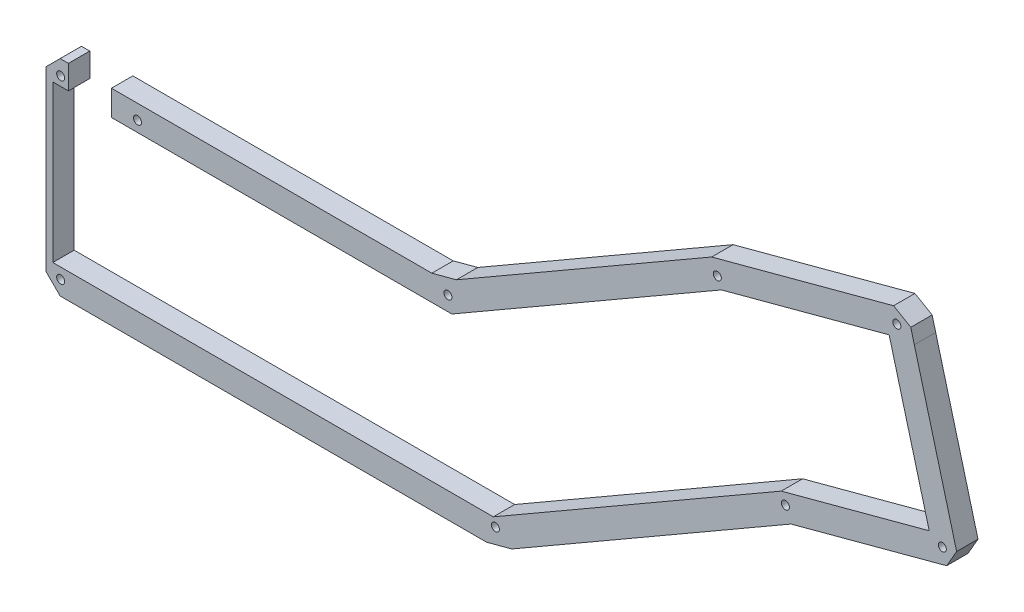
SolidWorks part; units mm, degrees
ref_plane "Plan de face" through (0, 0, 0) normal (0, 0, 1) x (1, 0, 0)
ref_plane "Plan de dessus" through (0, 0, 0) normal (0, 1, 0) x (1, 0, 0)
ref_plane "Plan de droite" through (0, 0, 0) normal (1, 0, 0) x (0, 0, -1)
sketch "Esquisse1" plane through (0, 0, 0) normal (0, 0, 1) x (1, 0, 0)
  line L0 (-73.9886, 18.0851) -> (-59.9886, 18.0851) construction
  line L1 (-73.9886, 37.0851) -> (-59.9886, 37.0851) construction
  line L2 (-73.9886, 37.0851) -> (-73.9886, 23.0851) construction
  line L3 (-73.9886, 23.0851) -> (-59.9886, 23.0851) construction
  line L4 (-59.9886, 37.0851) -> (-59.9886, 23.0851) construction
  line L5 (-73.9886, 18.0851) -> (-73.9886, 4.0851) construction
  line L6 (-73.9886, 4.0851) -> (-59.9886, 4.0851) construction
  line L7 (-59.9886, 18.0851) -> (-59.9886, 4.0851) construction
  line L8 (-73.9886, -0.9149) -> (-59.9886, -0.9149) construction
  line L9 (-73.9886, -0.9149) -> (-73.9886, -14.9149) construction
  line L10 (-73.9886, -14.9149) -> (-59.9886, -14.9149) construction
  line L11 (-59.9886, -0.9149) -> (-59.9886, -14.9149) construction
  line L12 (-73.9886, 37.0851) -> (-73.9886, 18.0851) construction
  line L13 (-54.9886, 18.0851) -> (-40.9886, 18.0851) construction
  line L14 (-54.9886, 37.0851) -> (-40.9886, 37.0851) construction
  line L15 (-54.9886, 37.0851) -> (-54.9886, 23.0851) construction
  line L16 (-54.9886, 23.0851) -> (-40.9886, 23.0851) construction
  line L17 (-40.9886, 37.0851) -> (-40.9886, 23.0851) construction
  line L18 (-54.9886, 18.0851) -> (-54.9886, 4.0851) construction
  line L19 (-54.9886, 4.0851) -> (-40.9886, 4.0851) construction
  line L20 (-40.9886, 18.0851) -> (-40.9886, 4.0851) construction
  line L21 (-54.9886, -0.9149) -> (-40.9886, -0.9149) construction
  line L22 (-54.9886, -0.9149) -> (-54.9886, -14.9149) construction
  line L23 (-54.9886, -14.9149) -> (-40.9886, -14.9149) construction
  line L24 (-40.9886, -0.9149) -> (-40.9886, -14.9149) construction
  line L25 (-54.9886, 37.0851) -> (-54.9886, 18.0851) construction
  line L26 (-35.9886, 18.0851) -> (-21.9886, 18.0851) construction
  line L27 (-35.9886, 37.0851) -> (-21.9886, 37.0851) construction
  line L28 (-35.9886, 37.0851) -> (-35.9886, 23.0851) construction
  line L29 (-35.9886, 23.0851) -> (-21.9886, 23.0851) construction
  line L30 (-21.9886, 37.0851) -> (-21.9886, 23.0851) construction
  line L31 (-35.9886, 18.0851) -> (-35.9886, 4.0851) construction
  line L32 (-35.9886, 4.0851) -> (-21.9886, 4.0851) construction
  line L33 (-21.9886, 18.0851) -> (-21.9886, 4.0851) construction
  line L34 (-35.9886, -0.9149) -> (-21.9886, -0.9149) construction
  line L35 (-35.9886, -0.9149) -> (-35.9886, -14.9149) construction
  line L36 (-35.9886, -14.9149) -> (-21.9886, -14.9149) construction
  line L37 (-21.9886, -0.9149) -> (-21.9886, -14.9149) construction
  line L38 (-35.9886, 37.0851) -> (-35.9886, 18.0851) construction
  line L39 (-16.9886, 18.0851) -> (-2.9886, 18.0851) construction
  line L40 (-16.9886, 37.0851) -> (-2.9886, 37.0851) construction
  line L41 (-16.9886, 37.0851) -> (-16.9886, 23.0851) construction
  line L42 (-16.9886, 23.0851) -> (-2.9886, 23.0851) construction
  line L43 (-2.9886, 37.0851) -> (-2.9886, 23.0851) construction
  line L44 (-16.9886, 18.0851) -> (-16.9886, 4.0851) construction
  line L45 (-16.9886, 4.0851) -> (-2.9886, 4.0851) construction
  line L46 (-2.9886, 18.0851) -> (-2.9886, 4.0851) construction
  line L47 (-16.9886, -0.9149) -> (-2.9886, -0.9149) construction
  line L48 (-16.9886, -0.9149) -> (-16.9886, -14.9149) construction
  line L49 (-16.9886, -14.9149) -> (-2.9886, -14.9149) construction
  line L50 (-2.9886, -0.9149) -> (-2.9886, -14.9149) construction
  line L51 (-16.9886, 37.0851) -> (-16.9886, 18.0851) construction
  line L52 (2.0114, 18.0851) -> (16.0114, 18.0851) construction
  line L53 (2.0114, 37.0851) -> (16.0114, 37.0851) construction
  line L54 (2.0114, 37.0851) -> (2.0114, 23.0851) construction
  line L55 (2.0114, 23.0851) -> (16.0114, 23.0851) construction
  line L56 (16.0114, 37.0851) -> (16.0114, 23.0851) construction
  line L57 (2.0114, 18.0851) -> (2.0114, 4.0851) construction
  line L58 (2.0114, 4.0851) -> (16.0114, 4.0851) construction
  line L59 (16.0114, 18.0851) -> (16.0114, 4.0851) construction
  line L60 (2.0114, -0.9149) -> (16.0114, -0.9149) construction
  line L61 (2.0114, -0.9149) -> (2.0114, -14.9149) construction
  line L62 (2.0114, -14.9149) -> (16.0114, -14.9149) construction
  line L63 (16.0114, -0.9149) -> (16.0114, -14.9149) construction
  line L64 (2.0114, 37.0851) -> (2.0114, 18.0851) construction
  line L65 (21.0114, 18.0851) -> (35.0114, 18.0851) construction
  line L66 (21.0114, 37.0851) -> (35.0114, 37.0851) construction
  line L67 (21.0114, 37.0851) -> (21.0114, 23.0851) construction
  line L68 (21.0114, 23.0851) -> (35.0114, 23.0851) construction
  line L69 (35.0114, 37.0851) -> (35.0114, 23.0851) construction
  line L70 (21.0114, 18.0851) -> (21.0114, 4.0851) construction
  line L71 (21.0114, 4.0851) -> (35.0114, 4.0851) construction
  line L72 (35.0114, 18.0851) -> (35.0114, 4.0851) construction
  line L73 (21.0114, -0.9149) -> (35.0114, -0.9149) construction
  line L74 (21.0114, -0.9149) -> (21.0114, -14.9149) construction
  line L75 (21.0114, -14.9149) -> (35.0114, -14.9149) construction
  line L76 (35.0114, -0.9149) -> (35.0114, -14.9149) construction
  line L77 (21.0114, 37.0851) -> (21.0114, 18.0851) construction
  line L78 (40.0114, 18.0851) -> (54.0114, 18.0851) construction
  line L79 (40.0114, 37.0851) -> (54.0114, 37.0851) construction
  line L80 (40.0114, 37.0851) -> (40.0114, 23.0851) construction
  line L81 (40.0114, 23.0851) -> (54.0114, 23.0851) construction
  line L82 (54.0114, 37.0851) -> (54.0114, 23.0851) construction
  line L83 (40.0114, 18.0851) -> (40.0114, 4.0851) construction
  line L84 (40.0114, 4.0851) -> (54.0114, 4.0851) construction
  line L85 (54.0114, 18.0851) -> (54.0114, 4.0851) construction
  line L86 (40.0114, -0.9149) -> (54.0114, -0.9149) construction
  line L87 (40.0114, -0.9149) -> (40.0114, -14.9149) construction
  line L88 (40.0114, -14.9149) -> (54.0114, -14.9149) construction
  line L89 (54.0114, -0.9149) -> (54.0114, -14.9149) construction
  line L90 (40.0114, 37.0851) -> (40.0114, 18.0851) construction
  line L91 (-73.9886, 18.0851) -> (-54.9886, 18.0851) construction
  line L92 (56.0114, 20.0851) -> (56.7532, 18.8002) construction
  line L93 (38.0114, 39.0851) -> (56.0114, 39.0851) construction
  line L94 (56.0114, 39.0851) -> (56.0114, 21.0851) construction
  line L95 (38.0114, 21.0851) -> (56.0114, 21.0851) construction
  line L96 (38.0114, 39.0851) -> (38.0114, 21.0851) construction
  line L97 (19.0114, 39.0851) -> (37.0114, 39.0851) construction
  line L98 (37.0114, 39.0851) -> (37.0114, 21.0851) construction
  line L99 (19.0114, 21.0851) -> (37.0114, 21.0851) construction
  line L100 (19.0114, 39.0851) -> (19.0114, 21.0851) construction
  line L101 (79.4363, 55.512) -> (88.4363, 39.9235) construction
  line L102 (88.4363, 39.9235) -> (72.8478, 30.9235) construction
  line L103 (63.8478, 46.512) -> (72.8478, 30.9235) construction
  line L104 (79.4363, 55.512) -> (63.8478, 46.512) construction
  line L105 (62.9818, 46.012) -> (71.9818, 30.4235) construction
  line L106 (71.9818, 30.4235) -> (56.3933, 21.4235) construction
  line L107 (47.3933, 37.012) -> (56.3933, 21.4235) construction
  line L108 (62.9818, 46.012) -> (47.3933, 37.012) construction
  line L109 (164.2542, 60.603) -> (148.6657, 51.603) construction
  line L110 (62.2497, 43.2799) -> (71.7497, 26.8254) construction
  line L111 (78.7042, 52.7799) -> (88.2042, 36.3254) construction
  line L112 (95.1587, 62.2799) -> (104.6587, 45.8254) construction
  line L113 (111.6132, 71.7799) -> (121.1132, 55.3254) construction
  line L114 (128.0677, 81.2799) -> (137.5677, 64.8254) construction
  line L115 (144.5221, 90.7799) -> (154.0221, 74.3254) construction
  line L116 (148.6657, 51.603) -> (157.6657, 36.0146) construction
  line L117 (69.1254, 3.371) -> (76.1254, -8.7534) construction
  line L118 (88.2497, -1.7534) -> (76.1254, -8.7534) construction
  line L119 (81.2497, 10.371) -> (88.2497, -1.7534) construction
  line L120 (81.2497, 10.371) -> (69.1254, 3.371) construction
  line L121 (59.6254, 19.8254) -> (66.6254, 7.7011) construction
  line L122 (78.7497, 14.7011) -> (66.6254, 7.7011) construction
  line L123 (71.7497, 26.8254) -> (78.7497, 14.7011) construction
  line L124 (50.1254, 36.2799) -> (57.1254, 24.1556) construction
  line L125 (69.2497, 31.1556) -> (57.1254, 24.1556) construction
  line L126 (62.2497, 43.2799) -> (69.2497, 31.1556) construction
  line L127 (62.2497, 43.2799) -> (50.1254, 36.2799) construction
  line L128 (71.7497, 26.8254) -> (59.6254, 19.8254) construction
  line L129 (85.5799, 12.871) -> (92.5799, 0.7466) construction
  line L130 (104.7042, 7.7466) -> (92.5799, 0.7466) construction
  line L131 (97.7042, 19.871) -> (104.7042, 7.7466) construction
  line L132 (97.7042, 19.871) -> (85.5799, 12.871) construction
  line L133 (76.0799, 29.3254) -> (83.0799, 17.2011) construction
  line L134 (95.2042, 24.2011) -> (83.0799, 17.2011) construction
  line L135 (88.2042, 36.3254) -> (95.2042, 24.2011) construction
  line L136 (66.5799, 45.7799) -> (73.5799, 33.6556) construction
  line L137 (85.7042, 40.6556) -> (73.5799, 33.6556) construction
  line L138 (78.7042, 52.7799) -> (85.7042, 40.6556) construction
  line L139 (78.7042, 52.7799) -> (66.5799, 45.7799) construction
  line L140 (88.2042, 36.3254) -> (76.0799, 29.3254) construction
  line L141 (102.0343, 22.371) -> (109.0343, 10.2466) construction
  line L142 (121.1587, 17.2466) -> (109.0343, 10.2466) construction
  line L143 (114.1587, 29.371) -> (121.1587, 17.2466) construction
  line L144 (114.1587, 29.371) -> (102.0343, 22.371) construction
  line L145 (92.5343, 38.8254) -> (99.5343, 26.7011) construction
  line L146 (111.6587, 33.7011) -> (99.5343, 26.7011) construction
  line L147 (104.6587, 45.8254) -> (111.6587, 33.7011) construction
  line L148 (83.0343, 55.2799) -> (90.0343, 43.1556) construction
  line L149 (102.1587, 50.1556) -> (90.0343, 43.1556) construction
  line L150 (95.1587, 62.2799) -> (102.1587, 50.1556) construction
  line L151 (95.1587, 62.2799) -> (83.0343, 55.2799) construction
  line L152 (104.6587, 45.8254) -> (92.5343, 38.8254) construction
  line L153 (118.4888, 31.871) -> (125.4888, 19.7466) construction
  line L154 (137.6132, 26.7466) -> (125.4888, 19.7466) construction
  line L155 (130.6132, 38.871) -> (137.6132, 26.7466) construction
  line L156 (130.6132, 38.871) -> (118.4888, 31.871) construction
  line L157 (108.9888, 48.3254) -> (115.9888, 36.2011) construction
  line L158 (128.1132, 43.2011) -> (115.9888, 36.2011) construction
  line L159 (121.1132, 55.3254) -> (128.1132, 43.2011) construction
  line L160 (99.4888, 64.7799) -> (106.4888, 52.6556) construction
  line L161 (118.6132, 59.6556) -> (106.4888, 52.6556) construction
  line L162 (111.6132, 71.7799) -> (118.6132, 59.6556) construction
  line L163 (111.6132, 71.7799) -> (99.4888, 64.7799) construction
  line L164 (121.1132, 55.3254) -> (108.9888, 48.3254) construction
  line L165 (134.9433, 41.371) -> (141.9433, 29.2466) construction
  line L166 (154.0677, 36.2466) -> (141.9433, 29.2466) construction
  line L167 (147.0677, 48.371) -> (154.0677, 36.2466) construction
  line L168 (147.0677, 48.371) -> (134.9433, 41.371) construction
  line L169 (125.4433, 57.8254) -> (132.4433, 45.7011) construction
  line L170 (144.5677, 52.7011) -> (132.4433, 45.7011) construction
  line L171 (137.5677, 64.8254) -> (144.5677, 52.7011) construction
  line L172 (115.9433, 74.2799) -> (122.9433, 62.1556) construction
  line L173 (135.0677, 69.1556) -> (122.9433, 62.1556) construction
  line L174 (128.0677, 81.2799) -> (135.0677, 69.1556) construction
  line L175 (128.0677, 81.2799) -> (115.9433, 74.2799) construction
  line L176 (137.5677, 64.8254) -> (125.4433, 57.8254) construction
  line L177 (151.3978, 50.871) -> (158.3978, 38.7466) construction
  line L178 (170.5221, 45.7466) -> (158.3978, 38.7466) construction
  line L179 (163.5221, 57.871) -> (170.5221, 45.7466) construction
  line L180 (163.5221, 57.871) -> (151.3978, 50.871) construction
  line L181 (141.8978, 67.3254) -> (148.8978, 55.2011) construction
  line L182 (161.0221, 62.2011) -> (148.8978, 55.2011) construction
  line L183 (154.0221, 74.3254) -> (161.0221, 62.2011) construction
  line L184 (132.3978, 83.7799) -> (139.3978, 71.6556) construction
  line L185 (151.5221, 78.6556) -> (139.3978, 71.6556) construction
  line L186 (144.5221, 90.7799) -> (151.5221, 78.6556) construction
  line L187 (144.5221, 90.7799) -> (132.3978, 83.7799) construction
  line L188 (154.0221, 74.3254) -> (141.8978, 67.3254) construction
  line L189 (173.2542, 45.0146) -> (157.6657, 36.0146) construction
  line L190 (164.2542, 60.603) -> (173.2542, 45.0146) construction
  line L191 (178.3169, 34.0986) -> (169.0534, 56.4627) construction
  line L192 (169.5193, 62.7839) -> (174.1781, 45.3972) construction
  line L193 (174.1781, 45.3972) -> (191.5647, 50.056) construction
  line L194 (186.906, 67.4426) -> (191.5647, 50.056) construction
  line L195 (162.1337, 98.0749) -> (167.0513, 79.7223) construction
  line L196 (169.5193, 62.7839) -> (186.906, 67.4426) construction
  line L197 (167.0513, 79.7223) -> (180.5742, 83.3457) construction
  line L198 (162.1337, 98.0749) -> (175.6567, 101.6983) construction
  line L199 (162.1337, 98.0749) -> (165.7572, 84.5519) construction
  line L200 (165.7572, 84.5519) -> (179.2801, 88.1754) construction
  line L201 (175.6567, 101.6983) -> (179.2801, 88.1754) construction
  line L202 (167.0513, 79.7223) -> (170.6747, 66.1993) construction
  line L203 (170.6747, 66.1993) -> (184.1977, 69.8228) construction
  line L204 (180.5742, 83.3457) -> (184.1977, 69.8228) construction
  line L205 (171.9688, 61.3697) -> (185.4918, 64.9932) construction
  line L206 (171.9688, 61.3697) -> (175.5923, 47.8467) construction
  line L207 (175.5923, 47.8467) -> (189.1152, 51.4702) construction
  line L208 (185.4918, 64.9932) -> (189.1152, 51.4702) construction
  line L209 (185.4038, 84.6398) -> (198.9268, 88.2633) construction
  line L210 (180.4863, 102.9924) -> (194.0092, 106.6159) construction
  line L211 (180.4863, 102.9924) -> (184.1097, 89.4695) construction
  line L212 (184.1097, 89.4695) -> (197.6327, 93.0929) construction
  line L213 (194.0092, 106.6159) -> (197.6327, 93.0929) construction
  line L214 (185.4038, 84.6398) -> (189.0273, 71.1169) construction
  line L215 (189.0273, 71.1169) -> (202.5503, 74.7403) construction
  line L216 (198.9268, 88.2633) -> (202.5503, 74.7403) construction
  line L217 (190.3214, 66.2873) -> (203.8444, 69.9107) construction
  line L218 (190.3214, 66.2873) -> (193.9449, 52.7643) construction
  line L219 (193.9449, 52.7643) -> (207.4678, 56.3878) construction
  line L220 (203.8444, 69.9107) -> (207.4678, 56.3878) construction
  line L221 (187.8719, 67.7015) -> (192.5307, 50.3148) construction
  line L222 (192.5307, 50.3148) -> (209.9173, 54.9735) construction
  line L223 (205.2586, 72.3602) -> (209.9173, 54.9735) construction
  line L224 (180.4863, 102.9924) -> (185.4038, 84.6398) construction
  line L225 (187.8719, 67.7015) -> (205.2586, 72.3602) construction
  line L226 (203.7564, 89.5574) -> (217.2794, 93.1809) construction
  line L227 (198.8389, 107.91) -> (212.3618, 111.5335) construction
  line L228 (198.8389, 107.91) -> (202.4623, 94.387) construction
  line L229 (202.4623, 94.387) -> (215.9853, 98.0105) construction
  line L230 (212.3618, 111.5335) -> (215.9853, 98.0105) construction
  line L231 (203.7564, 89.5574) -> (207.3799, 76.0344) construction
  line L232 (207.3799, 76.0344) -> (220.9029, 79.6579) construction
  line L233 (217.2794, 93.1809) -> (220.9029, 79.6579) construction
  line L234 (208.674, 71.2048) -> (222.197, 74.8283) construction
  line L235 (208.674, 71.2048) -> (212.2975, 57.6819) construction
  line L236 (212.2975, 57.6819) -> (225.8204, 61.3053) construction
  line L237 (222.197, 74.8283) -> (225.8204, 61.3053) construction
  line L238 (206.2245, 72.619) -> (210.8833, 55.2324) construction
  line L239 (210.8833, 55.2324) -> (228.2699, 59.8911) construction
  line L240 (223.6112, 77.2778) -> (228.2699, 59.8911) construction
  line L241 (198.8389, 107.91) -> (203.7564, 89.5574) construction
  line L242 (206.2245, 72.619) -> (223.6112, 77.2778) construction
  line L243 (167.0513, 79.7223) -> (185.4038, 84.6398) construction
  line L244 (38.0114, 20.0851) -> (56.0114, 20.0851) construction
  line L245 (56.0114, 20.0851) -> (56.0114, 2.0851) construction
  line L246 (38.0114, 2.0851) -> (56.0114, 2.0851) construction
  line L247 (38.0114, 20.0851) -> (38.0114, 2.0851) construction
  line L248 (72.4818, 29.5575) -> (56.8933, 20.5575) construction
  line L249 (56.8933, 20.5575) -> (65.8933, 4.969) construction
  line L250 (81.4818, 13.969) -> (65.8933, 4.969) construction
  line L251 (72.4818, 29.5575) -> (81.4818, 13.969) construction
  line L252 (56.8933, 20.5575) -> (57.6111, 19.3142) construction
  line L253 (164.6018, 81.1365) -> (169.2605, 63.7498) construction
  line L254 (169.2605, 63.7498) -> (186.6472, 68.4086) construction
  line L255 (181.9884, 85.7952) -> (186.6472, 68.4086) construction
  line L256 (164.6018, 81.1365) -> (181.9884, 85.7952) construction
  line L257 (154.7542, 77.0575) -> (163.7542, 61.469) construction
  line L258 (163.7542, 61.469) -> (148.1657, 52.469) construction
  line L259 (139.1657, 68.0575) -> (148.1657, 52.469) construction
  line L260 (154.7542, 77.0575) -> (139.1657, 68.0575) construction
  line L261 (196.3894, 109.3242) -> (213.776, 113.983) construction
  line L262 (-94.7538, 35.7952) -> (-76.7538, 35.7952) construction
  line L263 (-94.7538, 35.7952) -> (-94.7538, 2.7952) construction
  line L264 (-94.7538, 2.7952) -> (-76.7538, 2.7952) construction
  line L265 (-76.7538, 35.7952) -> (-76.7538, 2.7952) construction
  line L266 (213.776, 113.983) -> (218.4348, 96.5963) construction
  line L267 (201.0481, 91.9375) -> (218.4348, 96.5963) construction
  line L268 (196.3894, 109.3242) -> (201.0481, 91.9375) construction
  line L269 (-75.9886, -16.9149) -> (-57.9886, -16.9149) construction
  line L270 (-57.9886, 1.0851) -> (-57.9886, -16.9149) construction
  line L271 (-75.9886, 1.0851) -> (-57.9886, 1.0851) construction
  line L272 (-75.9886, 1.0851) -> (-75.9886, -16.9149) construction
  line L273 (38.0114, -16.9149) -> (56.0114, -16.9149) construction
  line L274 (56.0114, 1.0851) -> (56.0114, -16.9149) construction
  line L275 (38.0114, 1.0851) -> (56.0114, 1.0851) construction
  line L276 (38.0114, 1.0851) -> (38.0114, -16.9149) construction
  line L277 (-75.9886, 39.0851) -> (-57.9886, 39.0851) construction
  line L278 (-57.9886, 39.0851) -> (-57.9886, 21.0851) construction
  line L279 (-75.9886, 21.0851) -> (-57.9886, 21.0851) construction
  line L280 (-75.9886, 39.0851) -> (-75.9886, 21.0851) construction
  line L281 (145.2542, 93.512) -> (129.6657, 84.512) construction
  line L282 (129.6657, 84.512) -> (138.6657, 68.9235) construction
  line L283 (154.2542, 77.9235) -> (138.6657, 68.9235) construction
  line L284 (145.2542, 93.512) -> (154.2542, 77.9235) construction
  line L285 (223.4353, 116.5711) -> (228.0941, 99.1845) construction
  line L286 (148.2159, 106.7689) -> (211.1879, 123.6422) construction
  line L287 (177.5508, 35.9482) -> (235.6877, 51.5259) construction
  line L288 (177.5508, 35.9482) -> (72.9989, -24.4149) construction
  line L289 (-95.7538, -26.9149) -> (63.6687, -26.9149) construction
  line L290 (-100.7538, 35.7952) -> (-100.7538, -21.9149) construction
  line L291 (-75.9886, 49.0851) -> (43.3046, 49.0851) construction
  line L292 (148.2159, 106.7689) -> (52.6347, 51.5851) construction
  line L293 (-75.9886, 49.0851) -> (-57.9886, 49.0851) construction
  line L294 (140.2542, 102.1722) -> (124.6657, 93.1722) construction
  line L295 (193.8012, 118.9835) -> (211.1879, 123.6422) construction
  line L296 (213.4714, 45.5731) -> (230.8581, 50.2318) construction
  line L297 (38.0114, -26.9149) -> (38.0114, -85.4624) construction
  line L298 (178.2542, 36.3543) -> (162.6657, 27.3543) construction
  line L299 (38.0114, -26.9149) -> (56.0114, -26.9149) construction
  line L300 (-100.7538, 2.7952) -> (-100.7538, -38.0419) construction
  line L301 (-100.7538, 35.7952) -> (-100.7538, 2.7952) construction
  line L302 (-75.9886, 49.0851) -> (-95.7538, 49.0851) construction
  line L303 (-100.7538, 44.0851) -> (-100.7538, 35.7952) construction
  line L304 (211.1879, 123.6422) -> (216.0732, 124.9512) construction
  line L305 (222.1691, 121.4083) -> (223.4353, 116.5711) construction
  line L306 (228.0941, 99.1845) -> (239.2233, 57.6497) construction
  line L307 (216.0732, 124.9512) -> (222.1691, 121.4083) construction
  line L308 (235.6877, 51.5259) -> (239.2233, 57.6497) construction
  line L309 (63.6687, -26.9149) -> (72.9989, -24.4149) construction
  line L310 (52.6347, 51.5851) -> (43.3046, 49.0851) construction
  line L311 (-95.7538, 49.0851) -> (-100.7538, 44.0851) construction
  line L312 (-100.7538, -21.9149) -> (-95.7538, -26.9149) construction
  line L313 (-95.7538, 49.0851) -> (-95.7538, 44.0851) construction
  line L314 (-95.7538, 44.0851) -> (-100.7538, 44.0851) construction
  line L315 (-95.7538, -26.9149) -> (-95.7538, -21.9149) construction
  line L316 (68.3338, -25.6649) -> (67.0397, -20.8353) construction
  line L317 (47.9697, 50.3351) -> (49.2637, 45.5055) construction
  line L318 (177.5508, 35.9482) -> (175.6374, 40.5676) construction
  line L319 (148.2159, 106.7689) -> (150.1293, 102.1495) construction
  line L320 (239.2233, 57.6497) -> (234.3936, 56.3556) construction
  line L321 (216.0732, 124.9512) -> (217.3634, 120.1206) construction
  line L322 (-75.9886, 49.5851) -> (43.2388, 49.5851)
  line L323 (52.4417, 52.051) -> (43.2388, 49.5851)
  line L324 (148.0229, 107.2348) -> (52.4417, 52.051)
  line L325 (148.0229, 107.2348) -> (211.0584, 124.1252)
  line L326 (211.0584, 124.1252) -> (216.1447, 125.488)
  line L327 (216.1447, 125.488) -> (222.6001, 121.7361)
  line L328 (222.6001, 121.7361) -> (223.9186, 116.6992)
  line L329 (223.9186, 116.6992) -> (228.577, 99.3139)
  line L330 (228.577, 99.3139) -> (239.7598, 57.579)
  line L331 (236.0172, 51.0966) -> (239.7598, 57.579)
  line L332 (177.7438, 35.4823) -> (236.0172, 51.0966)
  line L333 (177.7438, 35.4823) -> (73.1918, -24.8808)
  line L334 (63.7346, -27.4149) -> (73.1918, -24.8808)
  line L335 (-95.9609, -27.4149) -> (63.7346, -27.4149)
  line L336 (-101.2538, -22.122) -> (-95.9609, -27.4149)
  line L337 (-101.2538, 35.7952) -> (-101.2538, -22.122)
  line L338 (-101.2538, 44.2922) -> (-101.2538, 35.7952)
  line L339 (-95.9609, 49.5851) -> (-101.2538, 44.2922)
  line L340 (-75.9886, 49.5851) -> (-76.7538, 49.5851)
  line L341 (2.0114, 40.0851) -> (52.7161, 40.0851)
  line L342 (151.6898, 98.3823) -> (50.7161, 40.0851)
  line L343 (-95.7538, 44.0851) -> (-63.3184, 44.0851) construction
  line L344 (-98.6986, -17.9149) -> (66.2572, -17.9149)
  line L345 (174.0769, 44.3349) -> (66.2572, -17.9149)
  line L346 (174.0769, 44.3349) -> (229.4947, 59.184)
  line L347 (214.4832, 115.2077) -> (229.4947, 59.184)
  line L348 (151.6898, 98.3823) -> (214.4832, 115.2077)
  line L349 (225.0947, 75.6047) -> (228.7182, 62.0818) construction
  line L350 (176.3687, 44.949) -> (189.8917, 48.5724) construction
  line L351 (89.7497, -4.3515) -> (77.6254, -11.3515) construction
  line L352 (-54.9886, -17.9149) -> (-40.9886, -17.9149) construction
  line L354 (2.0114, 40.0851) -> (16.0114, 40.0851) construction
  line L355 (77.2042, 55.378) -> (65.0799, 48.378) construction
  line L356 (179.7098, 105.8902) -> (193.2328, 109.5137) construction
  line L357 (2.0114, 40.0851) -> (-76.7538, 40.0851)
  line L358 (-76.7538, 40.0851) -> (-76.7538, 49.5851)
  line L360 (-98.6986, 40.6556) -> (-94.8608, 40.6556)
  line L361 (-94.8608, 40.6556) -> (-92.8618, 40.6556)
  line L362 (-94.8608, 49.5851) -> (-95.9609, 49.5851)
  line L363 (-66.9886, 37.0851) -> (-66.9886, 49.5851) construction
  line L364 (-75.9886, 49.5851) -> (-95.9609, 49.5851) construction
  line L365 (-92.8618, 40.6556) -> (-92.8618, 49.5851)
  line L366 (-76.7538, 39.0851) -> (-97.0101, 39.0851) construction
  line L367 (-76.7538, 39.0851) -> (-76.7538, 1.0851) construction
  line L368 (-76.7538, 1.0851) -> (-97.0101, 1.0851) construction
  line L369 (-97.0101, 39.0851) -> (-97.0101, 1.0851) construction
  line L370 (-92.8618, 49.5851) -> (-94.8608, 49.5851)
  line L371 (-98.6986, 40.6556) -> (-98.6986, -17.9149)
  circle A0 centre (-95.7538, 44.0851) radius 1.5
  circle A1 centre (-95.7538, -21.9149) radius 1.5
  circle A2 centre (67.0397, -20.8353) radius 1.5
  circle A3 centre (49.2637, 45.5055) radius 1.5
  circle A4 centre (175.6374, 40.5676) radius 1.5
  circle A5 centre (150.1293, 102.1495) radius 1.5
  circle A6 centre (234.3936, 56.3556) radius 1.5
  circle A7 centre (217.3634, 120.1206) radius 1.5
  circle A8 centre (-66.9886, 44.0851) radius 1.5
  point P304 (48.3046, 49.0851)
  point P305 (240.5174, 52.82)
  point P308 (68.6687, -26.9149)
  point P309 (-100.7538, -26.9149)
  point P311 (-100.7538, 49.0851)
  point P312 (220.9029, 126.2453)
  dimension "D32" = 3
  dimension "D33" = 5
  dimension "D40" = 5
  dimension "D41" = 5
  dimension "D42" = 5
  dimension "D43" = 5
  dimension "D44" = 0.5
  dimension "D1" = 14
  dimension "D2" = 14
  dimension "D4" = 19
  dimension "D6" = 19
  dimension "D7" = 30
  dimension "D10" = 1
  dimension "D11" = 2
  dimension "D13" = 0.5
  dimension "D15" = 2
  dimension "D12" = 7.5
  dimension "D14" = 19
  dimension "D18" = 2
  dimension "D20" = 18
  dimension "D21" = 33
  dimension "D22" = 2
  dimension "D8" = 2
  dimension "D9" = 2
  dimension "D16" = 2
  dimension "D19" = 2
  dimension "D23" = 2
  dimension "D24" = 10
  dimension "D25" = 10
  dimension "D26" = 10
  dimension "D27" = 10
  dimension "D28" = 10
  dimension "D29" = 6
  dimension "D30" = 10
  dimension "D31" = 10
  dimension "D45" = 3
  dimension "D46" = 3
  dimension "D48" = 3
  dimension "D49" = 3
  dimension "D50" = 3
  dimension "D51" = 3
  dimension "D52" = 3
  dimension "D3" = 3
  dimension "D5" = 7
  dimension "D17" = 3
extrude "Boss.-Extru.1" add sketch "Esquisse1" along normal blind 8
